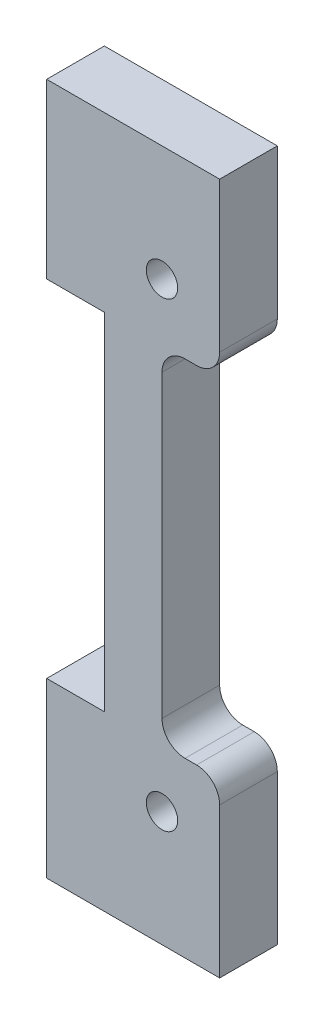
SolidWorks part; units mm, degrees
ref_plane "Front Plane" through (0, 0, 0) normal (0, 0, 1) x (1, 0, 0)
ref_plane "Top Plane" through (0, 0, 0) normal (0, 1, 0) x (1, 0, 0)
ref_plane "Right Plane" through (0, 0, 0) normal (1, 0, 0) x (0, 0, -1)
sketch "Sketch1" plane through (0, 0, 0) normal (0, 0, 1) x (1, 0, 0)
  line L0 (-107.95, -6.35) -> (-88.9, -6.35)
  line L1 (-95.25, -6.35) -> (44.45, -6.35) construction
  line L2 (-88.9, -6.35) -> (-88.9, 12.7)
  line L3 (-88.9, 12.7) -> (-95.25, 12.7)
  line L4 (-95.25, 12.7) -> (-95.25, 50.8)
  line L5 (-95.25, 50.8) -> (-88.9, 50.8)
  line L6 (-88.9, 50.8) -> (-88.9, 69.85)
  line L7 (-95.25, 69.85) -> (44.45, 69.85) construction
  line L8 (-88.9, 69.85) -> (-107.95, 69.85)
  line L9 (-107.95, 69.85) -> (-107.95, 50.8)
  line L10 (-107.95, 57.15) -> (-107.95, 6.35) construction
  line L11 (-107.95, 50.8) -> (-101.6, 50.8)
  line L12 (-101.6, 6.35) -> (-101.6, 57.15) construction
  line L13 (-101.6, 50.8) -> (-101.6, 12.7)
  line L14 (-101.6, 12.7) -> (-107.95, 12.7)
  line L15 (-107.95, 12.7) -> (-107.95, -6.35)
  dimension "D1" = 19.05
  dimension "D2" = 19.05
  dimension "D3" = 19.05
  dimension "D4" = 19.05
  dimension "D5" = 6.35
extrude "Boss-Extrude1" add sketch "Sketch1" against normal blind 6.35 from offset 6.35 offset against normal yes
fillet "Fillet1" radius 2.54 4 edges at (-88.9, 50.8, -9.525) (-95.25, 50.8, -9.525) (-95.25, 12.7, -9.525) (-88.9, 12.7, -9.525)
sketch "Sketch2" plane through (0, 0, -6.35) normal (0, 0, 1) x (1, 0, 0)
  line L0 (-95.25, 6.35) -> (-95.25, 57.15) construction
  line L1 (-95.25, 0) -> (-107.95, 0) construction
  line L2 (-107.95, 63.5) -> (-95.25, 63.5) construction
  line L3 (-88.9, -6.35) -> (-88.9, 10.16) construction
  circle A0 centre (-95.25, 6.35) radius 1.7272
  circle A1 centre (-95.25, 57.15) radius 1.7272
  dimension "D1" = 3.4544
  dimension "D2" = 6.35
  dimension "D3" = 6.35
  dimension "D4" = 6.35
extrude "Cut-Extrude1" cut sketch "Sketch2" against normal through all
